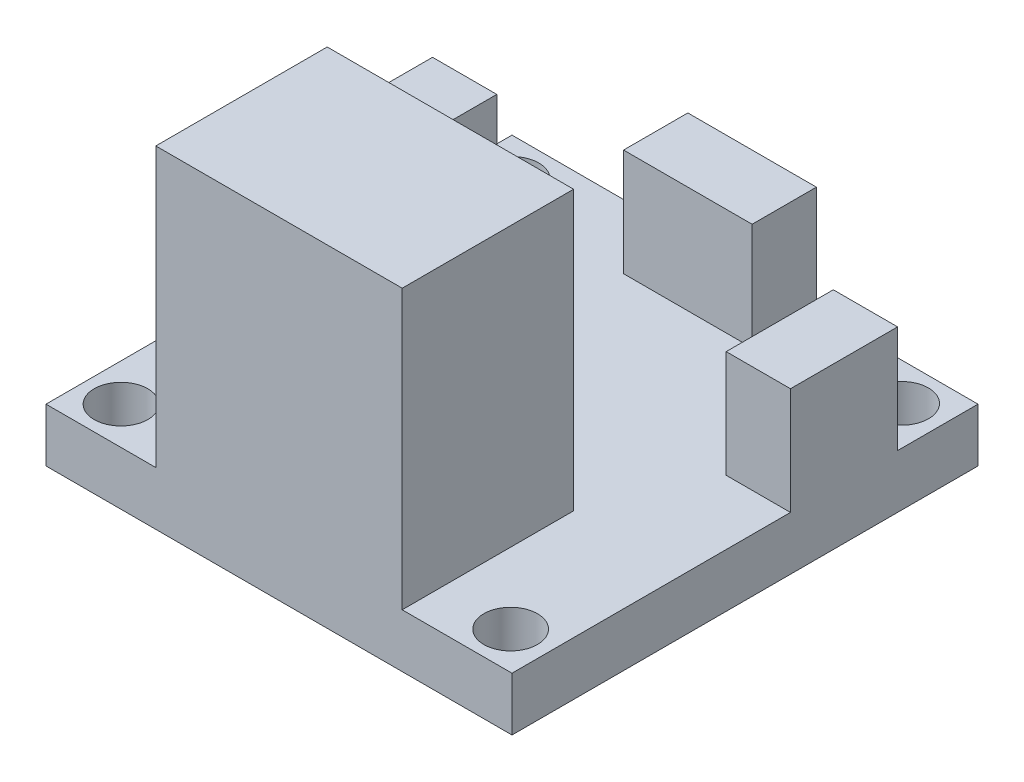
SolidWorks part; units mm, degrees
ref_plane "Front Plane" through (0, 0, 0) normal (0, 0, 1) x (1, 0, 0)
ref_plane "Top Plane" through (0, 0, 0) normal (0, 1, 0) x (1, 0, 0)
ref_plane "Right Plane" through (0, 0, 0) normal (1, 0, 0) x (0, 0, -1)
sketch "Sketch2" plane through (0, 0, 0) normal (0, 1, 0) x (1, 0, 0)
  line L1 (-21.75, 21.75) -> (21.75, 21.75)
  line L2 (-21.75, 21.75) -> (-21.75, -21.75)
  line L3 (-21.75, -21.75) -> (21.75, -21.75)
  line L4 (21.75, 21.75) -> (21.75, -21.75)
  line L5 (-21.75, 21.75) -> (21.75, -21.75) construction
  line L6 (-21.75, -21.75) -> (21.75, 21.75) construction
  point P0 (0, 0)
  dimension "D1" = 43.5
  dimension "D2" = 43.5
extrude "Boss-Extrude1" add sketch "Sketch2" along normal blind 5
sketch "Sketch4" plane through (0, 5, 0) normal (0, 1, 0) x (1, 0, 0)
  line L0 (-21.75, -21.75) -> (21.75, -21.75) construction
  line L1 (-11.5, -21.75) -> (11.5, -21.75)
  line L2 (-11.5, -21.75) -> (-11.5, -5.75)
  line L3 (-11.5, -5.75) -> (11.5, -5.75)
  line L4 (11.5, -21.75) -> (11.5, -5.75)
  line L5 (-21.75, 21.75) -> (-21.75, -21.75) construction
  dimension "D1" = 23
  dimension "D2" = 16
  dimension "D3" = 10.25
extrude "Boss-Extrude2" add sketch "Sketch4" along normal blind 26
sketch "Sketch5" plane through (0, 5, 0) normal (0, 1, 0) x (1, 0, 0)
  line L0 (-21.75, 21.75) -> (-21.75, -21.75) construction
  line L1 (-21.75, 14.3317) -> (-15.75, 14.3317)
  line L2 (-21.75, 14.3317) -> (-21.75, 4.3317)
  line L3 (-21.75, 4.3317) -> (-15.75, 4.3317)
  line L4 (-15.75, 14.3317) -> (-15.75, 4.3317)
  line L5 (21.75, 21.75) -> (-21.75, 21.75) construction
  line L6 (-5.3358, 21.75) -> (6.6642, 21.75)
  line L7 (-5.3358, 21.75) -> (-5.3358, 15.75)
  line L8 (-5.3358, 15.75) -> (6.6642, 15.75)
  line L9 (6.6642, 21.75) -> (6.6642, 15.75)
  line L10 (21.75, -21.75) -> (21.75, 21.75) construction
  line L11 (21.75, 14.2435) -> (15.75, 14.2435)
  line L12 (21.75, 14.2435) -> (21.75, 4.2435)
  line L13 (21.75, 4.2435) -> (15.75, 4.2435)
  line L14 (15.75, 14.2435) -> (15.75, 4.2435)
  dimension "D1" = 6
  dimension "D2" = 10
  dimension "D3" = 6
  dimension "D4" = 12
  dimension "D5" = 10
  dimension "D6" = 6
extrude "Boss-Extrude3" add sketch "Sketch5" along normal blind 10
sketch "Sketch6" plane through (0, 5, 0) normal (0, 1, 0) x (1, 0, 0)
  line L0 (-5.3358, 21.75) -> (-21.75, 21.75) construction
  line L1 (-21.75, 21.75) -> (-21.75, 14.3317) construction
  line L2 (-21.75, -21.75) -> (-11.5, -21.75) construction
  circle A0 centre (-18.25, 18.25) radius 2.5
  circle A1 centre (18.124, 18.25) radius 2.5
  circle A2 centre (18.124, -18.25) radius 2.5
  circle A3 centre (-18.25, -18.25) radius 2.5
  dimension "D1" = 5
  dimension "D2" = 3.5
  dimension "D3" = 3.5
  dimension "D4" = 3.5
extrude "Cut-Extrude1" cut sketch "Sketch6" against normal through all from offset 0
